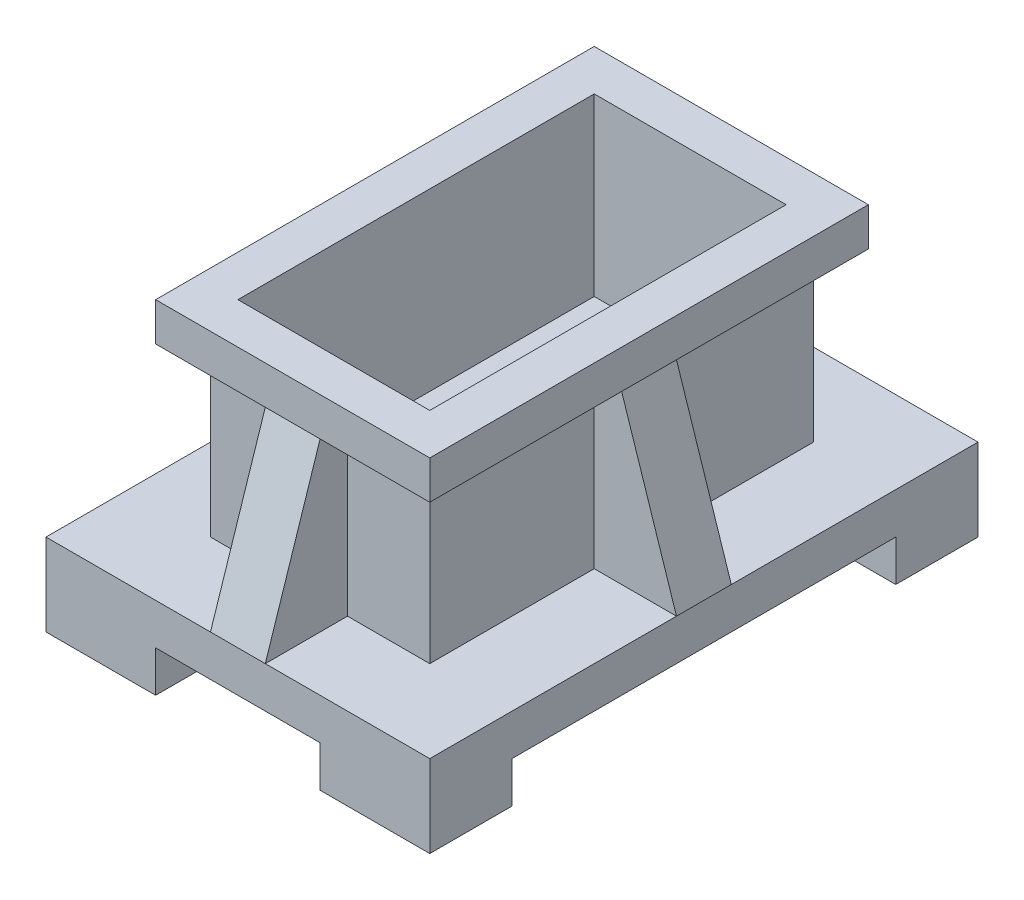
SolidWorks part; units mm, degrees
ref_plane "Front Plane" through (0, 0, 0) normal (0, 0, 1) x (1, 0, 0)
ref_plane "Top Plane" through (0, 0, 0) normal (0, 1, 0) x (1, 0, 0)
ref_plane "Right Plane" through (0, 0, 0) normal (1, 0, 0) x (0, 0, -1)
sketch "Sketch2" plane through (0, 0, 0) normal (0, 1, 0) x (1, 0, 0)
  line L1 (-70, -100) -> (70, -100)
  line L2 (-70, -100) -> (-70, 100)
  line L3 (-70, 100) -> (70, 100)
  line L4 (70, -100) -> (70, 100)
  line L5 (-70, -100) -> (70, 100) construction
  line L6 (-70, 100) -> (70, -100) construction
  point P0 (0, 0)
  dimension "D1" = 200
  dimension "D2" = 140
extrude "Boss-Extrude1" add sketch "Sketch2" along normal blind 30
sketch "Sketch3" plane through (0, 0, 100) normal (0, 0, 1) x (1, 0, 0)
  line L0 (-30, 0) -> (-30, 15)
  line L1 (-70, 0) -> (70, 0) construction
  line L2 (-30, 15) -> (30, 15)
  line L3 (30, 15) -> (30, 0)
  line L4 (30, 0) -> (-30, 0)
  line L5 (-70, 30) -> (-70, 0) construction
  line L6 (70, 30) -> (70, 0) construction
  point P8 (-30, 7.5)
  point P11 (30, 7.5)
  dimension "D1" = 40
  dimension "D2" = 40
  dimension "D3" = 15
extrude "Cut-Extrude1" cut sketch "Sketch3" against normal through all
sketch "Sketch4" plane through (70, 0, 0) normal (1, 0, 0) x (0, 0, -1)
  line L0 (-70, 0) -> (-70, 15)
  line L1 (-100, 0) -> (100, 0) construction
  line L2 (-70, 15) -> (70, 15)
  line L3 (70, 15) -> (70, 0)
  line L4 (70, 0) -> (-70, 0)
  line L5 (-100, 30) -> (-100, 0) construction
  line L6 (100, 30) -> (100, 0) construction
  point P4 (-70, 7.5)
  point P9 (-100, 15)
  point P10 (70, 7.5)
  dimension "D1" = 30
  dimension "D2" = 30
  dimension "D3" = 15
extrude "Cut-Extrude2" cut sketch "Sketch4" against normal through all
sketch "Sketch6" plane through (0, 30, 0) normal (0, 1, 0) x (1, 0, 0)
  line L14 (-40, -70) -> (40, -70)
  line L15 (40, -70) -> (40, 70)
  line L16 (40, 70) -> (-40, 70)
  line L17 (-40, 70) -> (-40, -70)
  line L18 (-40, -70) -> (40, -70)
  line L19 (40, -70) -> (40, 70)
  line L20 (40, 70) -> (-40, 70)
  line L21 (-40, 70) -> (-40, -70)
  dimension "D1" = 30
extrude "Boss-Extrude2" add sketch "Sketch6" along normal blind 61 contours L18 L19 L20 L21
sketch "Sketch12" plane through (0, 91, 0) normal (0, 1, 0) x (1, 0, 0)
  line L0 (-50, 80) -> (50, 80)
  line L7 (50, -80) -> (50, 80)
  line L8 (-50, -80) -> (50, -80)
  line L9 (-50, -80) -> (-50, 80)
  line L10 (-35, 65) -> (35, 65)
  line L11 (35, -65) -> (35, 65)
  line L12 (-35, -65) -> (35, -65)
  line L13 (-35, -65) -> (-35, 65)
  point P0 (0, 0)
extrude "Boss-Extrude3" add sketch "Sketch12" along normal blind 14
sketch "Sketch15" plane through (0, 91, 0) normal (0, 1, 0) x (1, 0, 0)
  line L1 (-35, -65) -> (35, -65)
  line L2 (-35, -65) -> (-35, 65)
  line L3 (-35, 65) -> (35, 65)
  line L4 (35, -65) -> (35, 65)
  line L5 (-35, -65) -> (35, 65) construction
  line L6 (-35, 65) -> (35, -65) construction
  point P0 (0, 0)
extrude "Cut-Extrude3" cut sketch "Sketch15" against normal blind 50
sketch "Sketch18" plane through (40, 0, 0) normal (1, 0, 0) x (0, 0, -1)
  line L3 (-24.0021, 17.2652) -> (-23.7448, 16.3569)
sketch "Sketch19" plane through (0, 30, 0) normal (0, 1, 0) x (1, 0, 0)
  line L0 (70, 0) -> (39.9378, 0)
  line L1 (70, -100) -> (70, 100) construction
  point P5 (0, 0)
sketch "Sketch23" plane through (0, 0, 0) normal (0, 0, 1) x (1, 0, 0)
  line L0 (-50, 91) -> (-70, 30)
  line L1 (-70, 30) -> (-40, 30)
  line L2 (-40, 30) -> (-40, 91)
  line L3 (-40, 91) -> (-50, 91)
extrude "Boss-Extrude4" add sketch "Sketch23" along normal mid plane 20
mirror "Mirror1" about plane through (0, 0, 0) normal (1, 0, 0) of "Boss-Extrude4"
sketch "Sketch24" plane through (0, 0, 0) normal (1, 0, 0) x (0, 0, -1)
  line L0 (-80, 91) -> (-100, 30)
  line L1 (-100, 30) -> (-70, 30)
  line L2 (-70, 30) -> (-70, 91)
  line L3 (-70, 91) -> (-80, 91)
extrude "Boss-Extrude5" add sketch "Sketch24" along normal mid plane 20
mirror "Mirror2" about plane through (0, 0, 0) normal (0, 0, 1) of "Boss-Extrude5"
